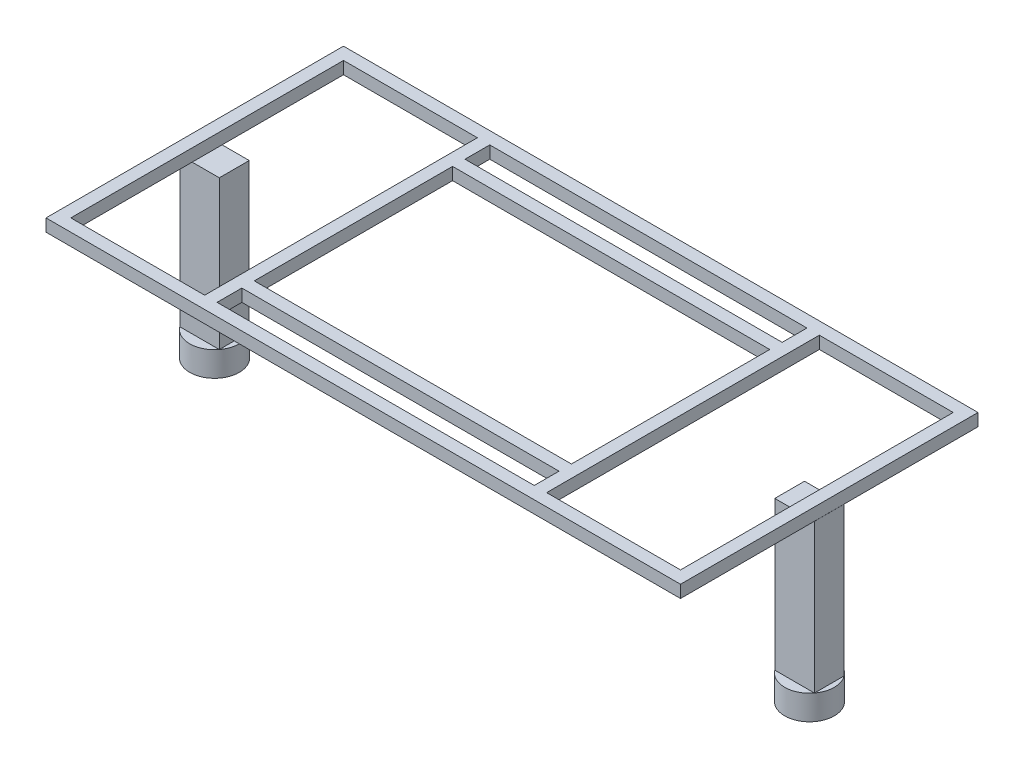
SolidWorks part; units mm, degrees
ref_plane "Front Plane" through (0, 0, 0) normal (0, 0, 1) x (1, 0, 0)
ref_plane "Top Plane" through (0, 0, 0) normal (0, 1, 0) x (1, 0, 0)
ref_plane "Right Plane" through (0, 0, 0) normal (1, 0, 0) x (0, 0, -1)
sketch "Sketch1" plane through (0, 0, 0) normal (0, 1, 0) x (1, 0, 0)
  circle A0 centre (304.8, 0) radius 25.4
  circle A1 centre (-304.8, 0) radius 25.4
  dimension "D1" = 50.8
  dimension "D2" = 304.8
  dimension "D3" = 304.8
extrude "Boss-Extrude1" add sketch "Sketch1" along normal blind 25.4
sketch "Sketch3" plane through (0, 25.4, 0) normal (0, 1, 0) x (1, 0, 0)
  line L1 (325.1219, -15.2375) -> (284.4781, -15.2375)
  line L2 (325.1219, -15.2375) -> (325.1219, 15.2375)
  line L3 (325.1219, 15.2375) -> (284.4781, 15.2375)
  line L4 (284.4781, -15.2375) -> (284.4781, 15.2375)
  line L5 (325.1219, -15.2375) -> (284.4781, 15.2375) construction
  line L6 (325.1219, 15.2375) -> (284.4781, -15.2375) construction
  circle A0 centre (304.8, 0) radius 25.4 construction
  point P0 (304.8, 0)
extrude "Boss-Extrude2" add sketch "Sketch3" along normal blind 152.4
sketch "Sketch4" plane through (0, 25.4, 0) normal (0, 1, 0) x (1, 0, 0)
  line L1 (-284.5538, -15.3379) -> (-325.0462, -15.3379)
  line L2 (-284.5538, -15.3379) -> (-284.5538, 15.3379)
  line L3 (-284.5538, 15.3379) -> (-325.0462, 15.3379)
  line L4 (-325.0462, -15.3379) -> (-325.0462, 15.3379)
  line L5 (-284.5538, -15.3379) -> (-325.0462, 15.3379) construction
  line L6 (-284.5538, 15.3379) -> (-325.0462, -15.3379) construction
  circle A0 centre (-304.8, 0) radius 25.4 construction
  point P0 (-304.8, 0)
extrude "Boss-Extrude3" add sketch "Sketch4" along normal blind 152.4
sketch "Sketch5" plane through (0, 177.8, 0) normal (0, 1, 0) x (1, 0, 0)
  line L0 (-284.5538, 0) -> (284.4781, 0) construction
  line L1 (-284.5538, -15.3379) -> (-284.5538, 15.3379) construction
  line L2 (284.4781, 15.2375) -> (284.4781, -15.2375) construction
  line L3 (-325.0462, 15.3379) -> (-325.0462, -15.3379) construction
  line L4 (325.0462, -152.4) -> (-325.0462, -152.4)
  line L5 (325.0462, -152.4) -> (325.0462, 152.4)
  line L6 (325.0462, 152.4) -> (-325.0462, 152.4)
  line L7 (-325.0462, -152.4) -> (-325.0462, 152.4)
  line L8 (325.0462, -152.4) -> (-325.0462, 152.4) construction
  line L9 (325.0462, 152.4) -> (-325.0462, -152.4) construction
  line L10 (-312.3462, -139.7) -> (-312.3462, 139.7)
  line L11 (312.3462, 139.7) -> (175.1862, 139.7)
  line L12 (312.3462, -139.7) -> (312.3462, 139.7)
  line L13 (312.3462, -139.7) -> (175.1862, -139.7)
  line L14 (0, 0) -> (0, -107.5) construction
  line L15 (175.1862, 139.7) -> (175.1862, -139.7)
  line L16 (162.4862, 139.7) -> (162.4862, 114.3)
  line L17 (-162.4862, 139.7) -> (-162.4862, 114.3)
  line L18 (-175.1862, 139.7) -> (-175.1862, -139.7)
  line L19 (-162.4862, 114.3) -> (162.4862, 114.3)
  line L20 (0, 0) -> (81.5954, 0) construction
  line L21 (-162.4862, 101.6) -> (162.4862, 101.6)
  line L22 (-162.4862, -101.6) -> (162.4862, -101.6)
  line L23 (-162.4862, -114.3) -> (162.4862, -114.3)
  line L24 (-175.1862, 139.7) -> (-312.3462, 139.7)
  line L25 (312.3462, 139.7) -> (-312.3462, 139.7) construction
  line L26 (-162.4862, 101.6) -> (-162.4862, -101.6)
  line L27 (162.4862, 139.7) -> (-162.4862, 139.7)
  line L28 (162.4862, 101.6) -> (162.4862, -101.6)
  line L29 (162.4862, -114.3) -> (162.4862, -139.7)
  line L30 (-162.4862, -114.3) -> (-162.4862, -139.7)
  line L31 (-175.1862, -139.7) -> (-312.3462, -139.7)
  line L32 (312.3462, -139.7) -> (-312.3462, -139.7) construction
  line L33 (162.4862, -139.7) -> (-162.4862, -139.7)
  point P6 (0, 0)
  dimension "D1" = 304.8
  dimension "D3" = 12.7
  dimension "D4" = 137.16
  dimension "D5" = 12.7
  dimension "D6" = 101.6
  dimension "D2" = 12.7
extrude "Boss-Extrude4" add sketch "Sketch5" along normal blind 12.7
